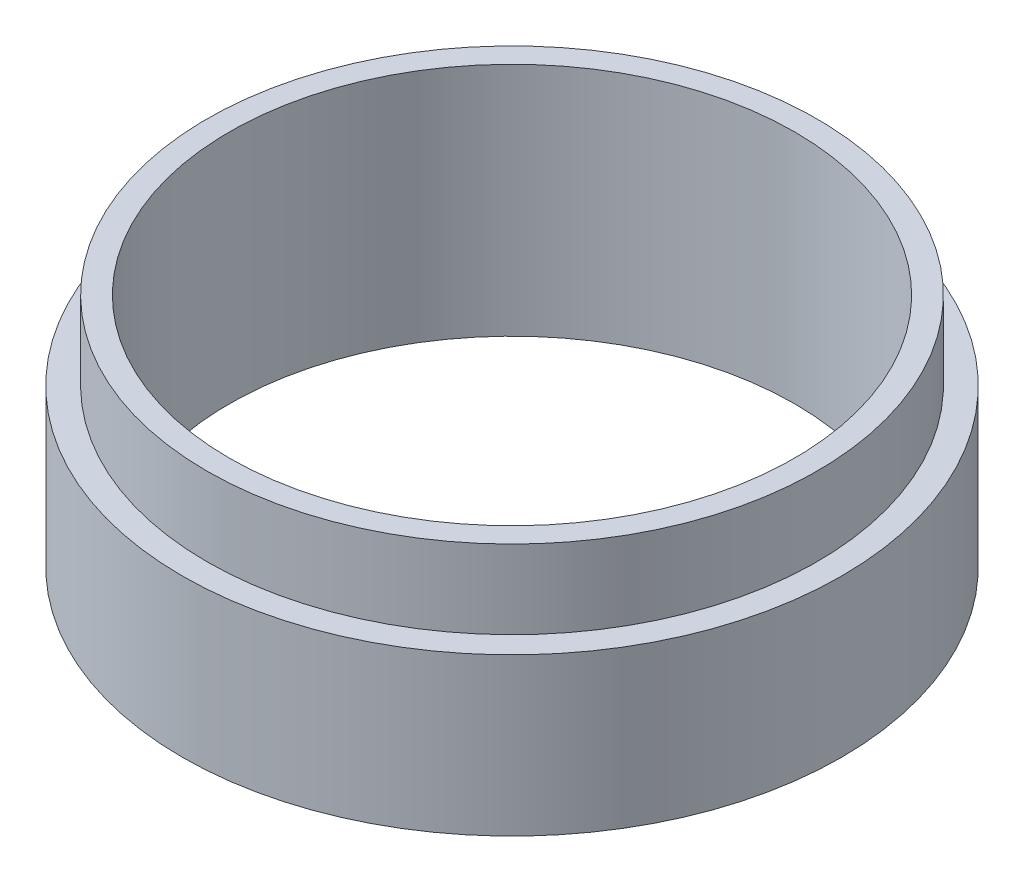
SolidWorks part; units mm, degrees
ref_plane "Front Plane" through (0, 0, 0) normal (0, 0, 1) x (1, 0, 0)
ref_plane "Top Plane" through (0, 0, 0) normal (0, 1, 0) x (1, 0, 0)
ref_plane "Right Plane" through (0, 0, 0) normal (1, 0, 0) x (0, 0, -1)
sketch "Sketch1" plane through (0, 0, 0) normal (0, 0, 1) x (1, 0, 0)
  line L0 (0, 0) -> (0, 23374.4256) construction
  line L1 (0, 0) -> (23374.4256, 0) construction
  line L3 (0, 10) -> (21, 10)
  line L4 (0, 10) -> (0, 0)
  line L5 (0, 0) -> (21, 0)
  line L6 (21, 10) -> (21, 0)
  line L7 (0, 10) -> (21, 0) construction
  line L8 (0, 0) -> (21, 10) construction
  point P5 (10.5, 5)
  dimension "D1" = 42
  dimension "D2" = 10
revolve "Revolve1" add sketch "Sketch1" angle 360 about L0
sketch "Sketch2" plane through (0, 10, 0) normal (0, 1, 0) x (1, 0, 0)
  circle A2 centre (0, 0) radius 18
  circle A3 centre (0, 0) radius 18
  dimension "D1" = 3
extrude "Cut-Extrude1" cut sketch "Sketch2" against normal through all
sketch "Sketch4" plane through (0, 10, 0) normal (0, 1, 0) x (1, 0, 0)
  circle A3 centre (0, 0) radius 19.43
  circle A4 centre (0, 0) radius 19.43
  dimension "D1" = 1.43
extrude "Boss-Extrude1" add sketch "Sketch4" along normal blind 5
sketch "Sketch5" plane through (0, 15, 0) normal (0, 1, 0) x (1, 0, 0)
  circle A2 centre (0, 0) radius 18
  circle A3 centre (0, 0) radius 18
  dimension "D1" = 3
extrude "Cut-Extrude2" cut sketch "Sketch5" against normal through all
